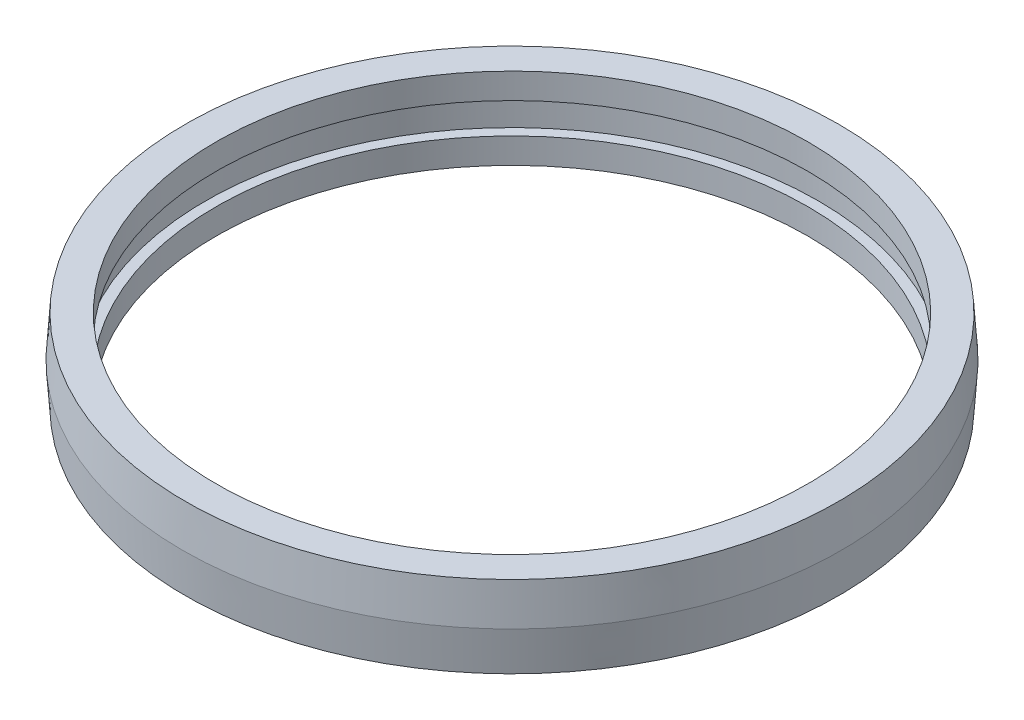
SolidWorks part; units mm, degrees
material "Rubber"
ref_plane "Front" through (0, 0, 0) normal (0, 0, 1) x (1, 0, 0)
ref_plane "Top" through (0, 0, 0) normal (0, 1, 0) x (1, 0, 0)
ref_plane "Right" through (0, 0, 0) normal (1, 0, 0) x (0, 0, -1)
sketch "Sketch3" plane through (0, 0, 0) normal (0, 0, 1) x (1, 0, 0)
  line L0 (0, 0) -> (0, 45.3916) construction
  line L2 (-102.4881, 0) -> (0, 0) construction
  line L18 (-92.075, -4.7625) -> (-95.25, -4.7625)
  line L19 (-95.25, -4.7625) -> (-95.25, 4.7625)
  line L20 (-95.25, 4.7625) -> (-92.075, 4.7625)
  line L21 (-92.075, 4.7625) -> (-92.075, 12.7)
  line L22 (-92.075, 12.7) -> (-101.6, 12.7)
  line L23 (-101.6, 12.7) -> (-102.4881, 0)
  line L24 (-102.4881, 0) -> (-101.6, -12.7)
  line L25 (-101.6, -12.7) -> (-92.075, -12.7)
  line L26 (-92.075, -12.7) -> (-92.075, -4.7625)
  dimension "D1" = 92.075
  dimension "D2" = 9.525
  dimension "D3" = 25.4
  dimension "D4" = 95.25
  dimension "D5" = 9.525
  dimension "D6" = 12.7
  dimension "D7" = 10.4131
  dimension "D8" = 7.9375
  dimension "D9" = 102.4881
  dimension "D10" = 3.175
revolve "Revolve1" add sketch "Sketch3" angle 360 about L0
